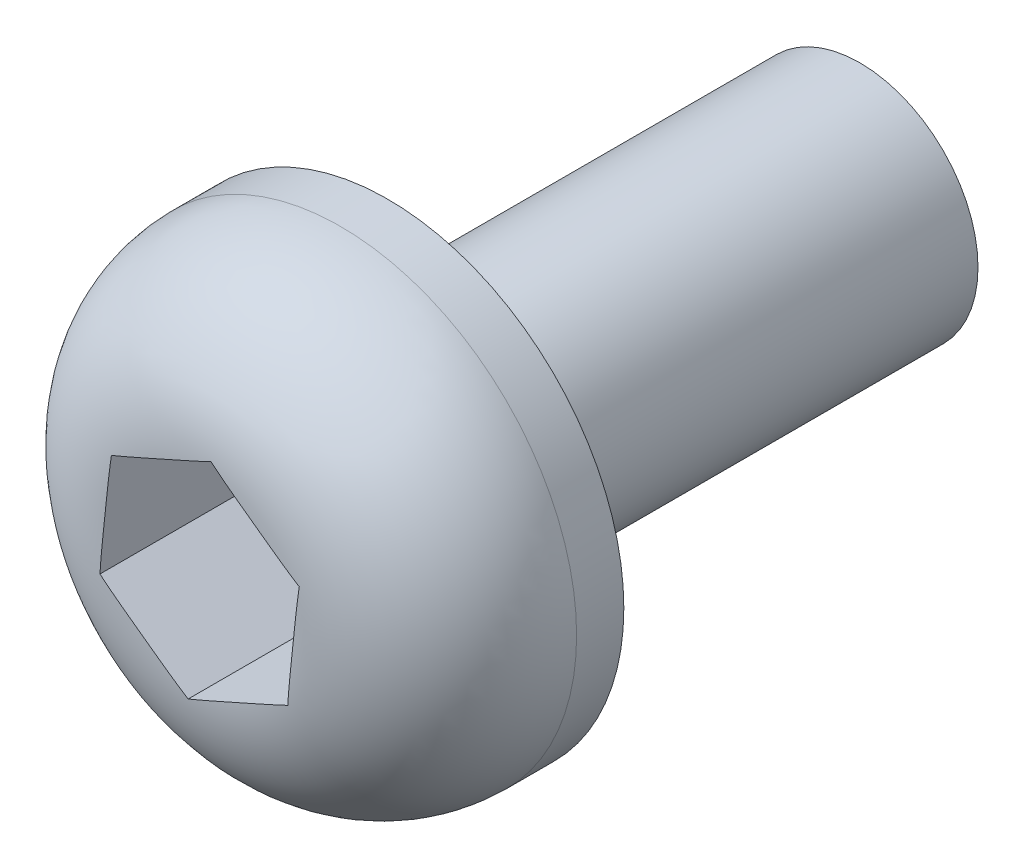
SolidWorks part; units mm, degrees
ref_plane "前视基准面" through (0, 0, 0) normal (0, 0, 1) x (1, 0, 0)
ref_plane "上视基准面" through (0, 0, 0) normal (0, 1, 0) x (1, 0, 0)
ref_plane "右视基准面" through (0, 0, 0) normal (1, 0, 0) x (0, 0, -1)
sketch "草图1" plane through (0, 0, 0) normal (0, 0, 1) x (1, 0, 0)
  circle A0 centre (0, 0) radius 2.5
  dimension "D1" = 5
extrude "凸台-拉伸1" add sketch "草图1" along normal blind 10
sketch "草图2" plane through (0, 0, 10) normal (0, 0, 1) x (1, 0, 0)
  circle A0 centre (0, 0) radius 5
  dimension "D1" = 10
extrude "凸台-拉伸2" add sketch "草图2" along normal blind 4
fillet "圆角1" radius 3 1 edges at (5, 0, 14)
sketch "草图3" plane through (0, 0, 14) normal (0, 0, 1) x (1, 0, 0)
  line L1 (-0.2424, -2.2966) -> (1.8678, -1.3582)
  line L2 (1.8678, -1.3582) -> (2.1101, 0.9384)
  line L3 (2.1101, 0.9384) -> (0.2424, 2.2966)
  line L4 (0.2424, 2.2966) -> (-1.8678, 1.3582)
  line L5 (-1.8678, 1.3582) -> (-2.1101, -0.9384)
  line L6 (-2.1101, -0.9384) -> (-0.2424, -2.2966)
  circle A0 centre (0, 0) radius 2 construction
  dimension "D1" = 4
extrude "切除-拉伸1" cut sketch "草图3" against normal blind 3
